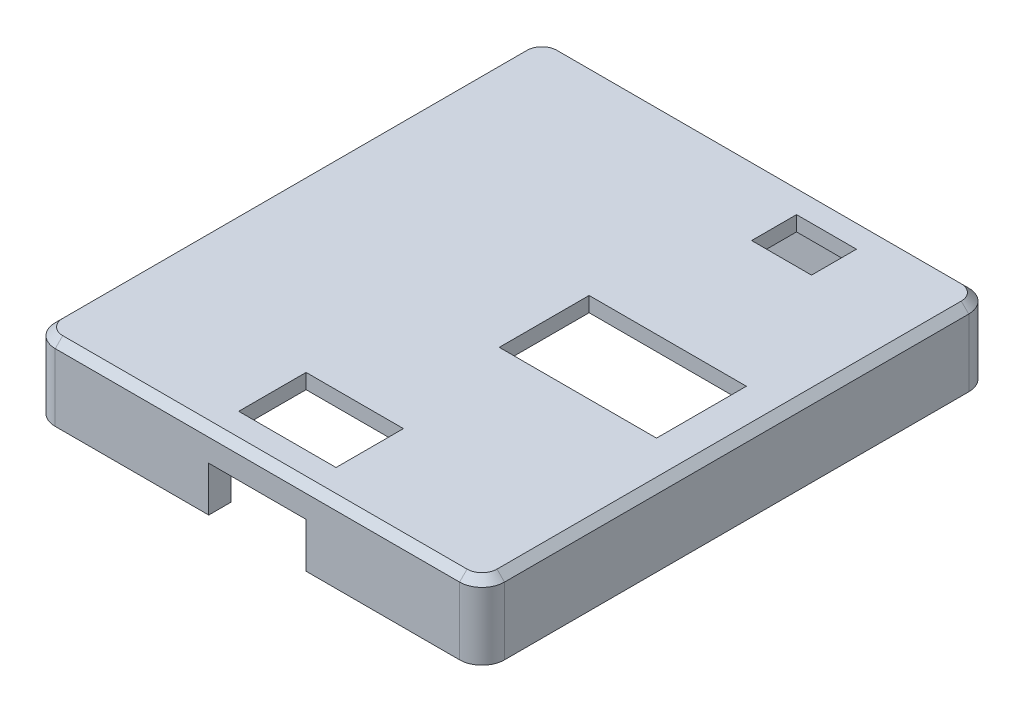
SolidWorks part; units mm, degrees
ref_plane "Front Plane" through (0, 0, 0) normal (0, 0, 1) x (1, 0, 0)
ref_plane "Top Plane" through (0, 0, 0) normal (0, 1, 0) x (1, 0, 0)
ref_plane "Right Plane" through (0, 0, 0) normal (1, 0, 0) x (0, 0, -1)
sketch "Sketch1" plane through (0, 0, 0) normal (0, 1, 0) x (1, 0, 0)
  line L1 (0, 0) -> (76.2, 0)
  line L2 (0, 0) -> (0, 86.36)
  line L3 (0, 86.36) -> (76.2, 86.36)
  line L4 (76.2, 0) -> (76.2, 86.36)
  dimension "D1" = 76.2
  dimension "D2" = 86.36
extrude "Boss-Extrude1" add sketch "Sketch1" along normal blind 12.7
fillet "Fillet1" radius 3.81 4 edges at (0, 6.35, -86.36) (76.2, 6.35, -86.36) (76.2, 6.35, 0) (0, 6.35, 0)
chamfer "Chamfer1" distance 1.27 angle 45 8 edges at (76.2, 12.7, -43.18) (75.0841, 12.7, -85.2441) (75.0841, 12.7, -1.1159) (38.1, 12.7, -86.36) (38.1, 12.7, 0) (1.1159, 12.7, -85.2441) (1.1159, 12.7, -1.1159) (0, 12.7, -43.18)
sketch "Sketch4" plane through (0, 0, 0) normal (0, -1, 0) x (1, 0, 0)
  line L4 (38.1, -3.81) -> (38.1, -82.55) construction
  line L7 (3.81, -16.51) -> (16.51, -16.51)
  line L8 (3.81, -3.81) -> (3.81, -82.55)
  line L9 (3.81, -82.55) -> (72.39, -82.55)
  line L10 (72.39, -82.55) -> (72.39, -3.81)
  line L11 (72.39, -3.81) -> (3.81, -3.81)
  line L12 (3.81, -16.51) -> (3.81, -69.85)
  line L13 (16.51, -82.55) -> (59.69, -82.55)
  line L14 (72.39, -69.85) -> (72.39, -16.51)
  line L15 (59.69, -3.81) -> (16.51, -3.81)
  line L16 (16.51, -3.81) -> (16.51, -16.51)
  line L17 (38.1, -82.55) -> (3.81, -43.18) construction
  line L18 (3.81, -43.18) -> (72.39, -43.18) construction
  line L19 (72.39, -16.51) -> (59.69, -16.51)
  line L20 (59.69, -3.81) -> (59.69, -16.51)
  line L24 (59.69, -82.55) -> (59.69, -69.85)
  line L25 (72.39, -69.85) -> (59.69, -69.85)
  line L27 (3.81, -69.85) -> (16.51, -69.85)
  line L28 (16.51, -82.55) -> (16.51, -69.85)
  dimension "D2" = 12.7
  dimension "D3" = 12.7
  dimension "D1" = 3.81
extrude "Cut-Extrude1" cut sketch "Sketch4" against normal blind 10.16
sketch "Sketch5" plane through (0, 12.7, 0) normal (0, 1, 0) x (1, 0, 0)
  line L0 (72.39, 0) -> (3.81, 0) construction
  line L1 (29.845, 5.08) -> (46.355, 5.08)
  line L2 (29.845, 5.08) -> (29.845, 16.51)
  line L3 (29.845, 16.51) -> (46.355, 16.51)
  line L4 (46.355, 5.08) -> (46.355, 16.51)
  line L5 (0, 3.81) -> (0, 82.55) construction
  point P6 (38.1, 16.51)
  dimension "D1" = 5.08
  dimension "D2" = 11.43
  dimension "D3" = 16.51
  dimension "D4" = 38.1
extrude "Cut-Extrude2" cut sketch "Sketch5" against normal blind 2.54
sketch "Sketch6" plane through (0, 0, 0) normal (0, 0, 1) x (1, 0, 0)
  line L0 (41.91, 0) -> (-41.91, 0) construction
  line L1 (29.845, 0) -> (46.355, 0)
  line L2 (29.845, 0) -> (29.845, 7.62)
  line L3 (29.845, 7.62) -> (46.355, 7.62)
  line L4 (46.355, 0) -> (46.355, 7.62)
  line L5 (76.2, 11.43) -> (76.2, 0) construction
  point P6 (38.1, 7.62)
  dimension "D1" = 16.51
  dimension "D2" = 38.1
  dimension "D3" = 7.62
extrude "Cut-Extrude3" cut sketch "Sketch6" against normal up to next
sketch "Sketch8" plane through (0, 0, -86.36) normal (0, 0, -1) x (-1, 0, 0)
  line L0 (41.91, 0) -> (-41.91, 0) construction
  line L1 (-42.164, 0) -> (-34.036, 0)
  line L2 (-42.164, 0) -> (-42.164, 1.27)
  line L3 (-42.164, 1.27) -> (-34.036, 1.27)
  line L4 (-34.036, 0) -> (-34.036, 1.27)
  line L5 (0, 11.43) -> (0, 0) construction
  point P6 (-38.1, 1.27)
  dimension "D1" = 8.128
  dimension "D2" = 38.1
  dimension "D3" = 1.27
extrude "Cut-Extrude4" cut sketch "Sketch8" against normal up to next
sketch "Sketch9" plane through (0, 0, -86.36) normal (0, 0, -1) x (-1, 0, 0)
  line L0 (41.91, 0) -> (-41.91, 0) construction
  line L1 (-58.42, 0) -> (-48.26, 0)
  line L2 (-58.42, 0) -> (-58.42, 3.81)
  line L3 (-58.42, 3.81) -> (-48.26, 3.81)
  line L4 (-48.26, 0) -> (-48.26, 3.81)
  line L5 (-76.2, 0) -> (-76.2, 11.43) construction
  point P6 (-58.42, 1.905)
  dimension "D1" = 17.78
  dimension "D2" = 10.16
  dimension "D3" = 3.81
extrude "Cut-Extrude5" cut sketch "Sketch9" against normal up to next
sketch "Sketch10" plane through (0, 12.7, 0) normal (0, 1, 0) x (1, 0, 0)
  line L0 (76.2, 82.55) -> (76.2, 3.81) construction
  line L1 (58.42, 81.28) -> (48.26, 81.28)
  line L2 (58.42, 81.28) -> (58.42, 73.66)
  line L3 (58.42, 73.66) -> (48.26, 73.66)
  line L4 (48.26, 81.28) -> (48.26, 73.66)
  line L5 (3.81, 86.36) -> (72.39, 86.36) construction
  dimension "D1" = 17.78
  dimension "D2" = 5.08
  dimension "D3" = 10.16
  dimension "D4" = 7.62
extrude "Cut-Extrude6" cut sketch "Sketch10" against normal up to next
sketch "Sketch11" plane through (0, 12.7, 0) normal (0, 1, 0) x (1, 0, 0)
  line L0 (76.2, 82.55) -> (76.2, 3.81) construction
  line L1 (42.545, 51.816) -> (69.215, 51.816)
  line L2 (42.545, 51.816) -> (42.545, 36.576)
  line L3 (42.545, 36.576) -> (69.215, 36.576)
  line L4 (69.215, 51.816) -> (69.215, 36.576)
  line L5 (72.39, 0) -> (3.81, 0) construction
  dimension "D1" = 6.985
  dimension "D2" = 36.576
  dimension "D3" = 26.67
  dimension "D4" = 15.24
extrude "Cut-Extrude7" cut sketch "Sketch11" against normal up to next
hole_wizard "1/4-20 Tapped Hole1" positions "3DSketch2" profile "Sketch12" tap size "1/4-20" standard "ANSI Inch"
sketch3d "3DSketch2"
  line L0 (0, 0, -82.55) -> (0, 0, -3.81) construction
  line L1 (3.81, 0, 0) -> (29.845, 0, 0) construction
  line L2 (34.036, 0, -86.36) -> (3.81, 0, -86.36) construction
  line L3 (72.39, 0, -86.36) -> (58.42, 0, -86.36) construction
  line L5 (76.2, 0, -3.81) -> (76.2, 0, -82.55) construction
  line L6 (46.355, 0, 0) -> (72.39, 0, 0) construction
  point P0 (10.16, 0, -10.16)
  point P2 (10.16, 0, -76.2)
  point P4 (66.04, 0, -76.2)
  point P6 (66.04, 0, -10.16)
  dimension "D1" = 10.16
  dimension "D2" = 10.16
  dimension "D3" = 10.16
  dimension "D4" = 10.16
  dimension "D5" = 10.16
  dimension "D6" = 10.16
  dimension "D7" = 10.16
  dimension "D8" = 10.16
sketch "Sketch12" plane through (10.16, 0, -10.16) normal (1, 0, 0) x (0, 0, -1)
  line L0 (0, 0) -> (0, 7.8838)
  line L1 (0, 7.8838) -> (2.5527, 6.35)
  line L2 (2.5527, 6.35) -> (2.5527, 0)
  line L5 (2.5527, 0) -> (0, 0)
  line L10 (0, 7.8838) -> (-2.5527, 6.35) construction
  line L11 (0, -6.35) -> (0, 107.95) construction
  dimension "Tap Drill Dia." = 5.1054
  dimension "Tap Drill Depth" = 6.35
  dimension "Drill Angle" = 118
cosmetic thread "Hole Thread1" parameters "D1"=12.7, "D2"=6.35
cosmetic thread "Hole Thread2" parameters "D1"=12.7, "D2"=6.35
cosmetic thread "Hole Thread3" parameters "D1"=12.7, "D2"=6.35
cosmetic thread "Hole Thread4" parameters "D1"=12.7, "D2"=6.35
equation "\"0.05n\"=0.1"
